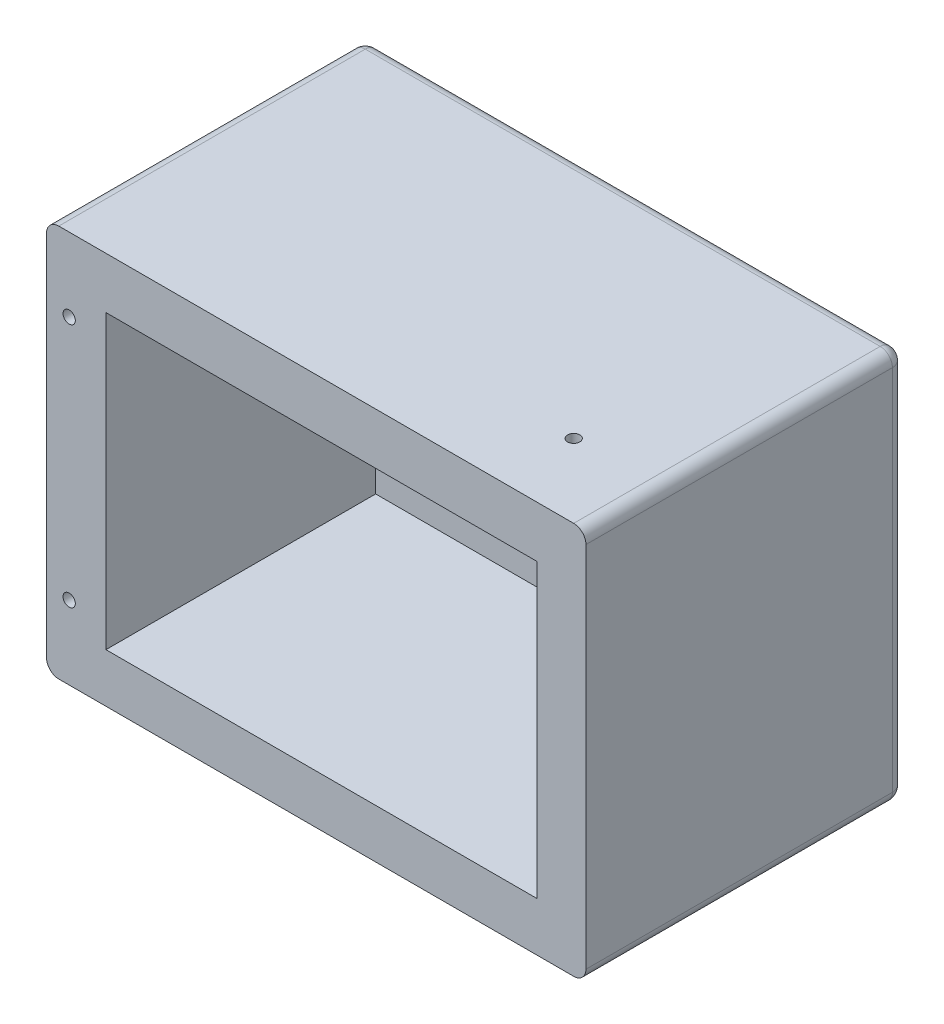
SolidWorks part; units mm, degrees
ref_plane "前视基准面" through (0, 0, 0) normal (0, 0, 1) x (1, 0, 0)
ref_plane "上视基准面" through (0, 0, 0) normal (0, 1, 0) x (1, 0, 0)
ref_plane "右视基准面" through (0, 0, 0) normal (1, 0, 0) x (0, 0, -1)
other "Configuration Table"
sketch "草图1" plane through (0, 0, 0) normal (0, 0, 1) x (1, 0, 0)
  line L0 (0, 0) -> (440, 0)
  line L1 (440, 0) -> (440, -320)
  line L2 (440, -320) -> (0, -320)
  line L3 (0, -320) -> (0, 0)
  dimension "D1" = 440
  dimension "D2" = 320
extrude "凸台-拉伸1" add sketch "草图1" along normal blind 260
sketch "草图6" plane through (0, 0, 260) normal (0, 0, 1) x (1, 0, 0)
  line L0 (440, -320) -> (440, 0) construction
  line L1 (48.4708, -41.8673) -> (400, -41.8673)
  line L2 (48.4708, -41.8673) -> (48.4708, -280)
  line L3 (48.4708, -280) -> (400, -280)
  line L4 (400, -41.8673) -> (400, -280)
  line L6 (0, -320) -> (440, -320) construction
  dimension "D1" = 40
  dimension "D2" = 40
extrude "切除-拉伸1" cut sketch "草图6" against normal blind 220
fillet "圆角1" radius 10 8 edges at (220, -320, 0) (220, 0, 0) (0, -160, 0) (0, 0, 130) (0, -320, 130) (440, -320, 130) (440, -160, 0) (440, 0, 130)
sketch "草图7" plane through (0, 0, 260) normal (0, 0, 1) x (1, 0, 0)
  line L0 (430, 0) -> (10, 0) construction
  line L1 (10, -320) -> (430, -320) construction
  line L2 (48.4708, -41.8673) -> (48.4708, -280) construction
  line L3 (48.4708, -41.8673) -> (48.4708, -280) construction
  circle A0 centre (18.4708, -60) radius 5
  circle A1 centre (18.4708, -260) radius 5
  point P13 (18.4708, -260)
  point P14 (18.4708, -60)
  dimension "D1" = 10
  dimension "D2" = 10
  dimension "D3" = 60
  dimension "D4" = 60
  dimension "D5" = 30
  dimension "D6" = 30
extrude "切除-拉伸2" cut sketch "草图7" against normal blind 10
sketch "草图8" plane through (0, 0, 0) normal (0, 1, 0) x (1, 0, 0)
  line L0 (430, -260) -> (10, -260) construction
  line L1 (430, -260) -> (430, -10) construction
  circle A0 centre (370, -200) radius 5
  dimension "D1" = 10
  dimension "D2" = 60
  dimension "D3" = 60
extrude "切除-拉伸3" cut sketch "草图8" against normal blind 10
